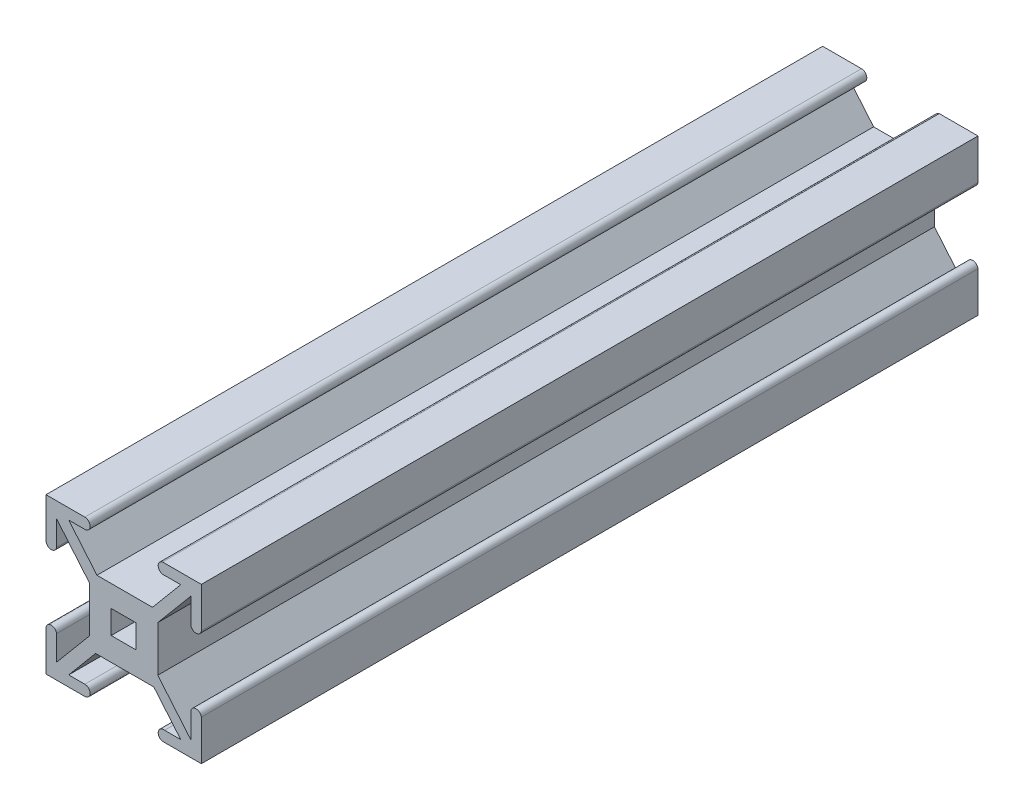
SolidWorks part; units mm, degrees
ref_plane "Front Plane" through (0, 0, 0) normal (0, 0, 1) x (1, 0, 0)
ref_plane "Top Plane" through (0, 0, 0) normal (0, 1, 0) x (1, 0, 0)
ref_plane "Right Plane" through (0, 0, 0) normal (1, 0, 0) x (0, 0, -1)
sketch "Sketch1" plane through (0, 0, 0) normal (0, 0, 1) x (1, 0, 0)
  line L1 (-21.0591, 25) -> (28.9409, 25)
  line L2 (-21.0591, 25) -> (-21.0591, -25)
  line L3 (-21.0591, -25) -> (28.9409, -25)
  line L4 (28.9409, 25) -> (28.9409, -25)
  dimension "D1" = 50
  dimension "D2" = 50
extrude "Boss-Extrude1" add sketch "Sketch1" along normal blind 250
sketch "Sketch2" plane through (0, 0, 0) normal (0, 0, -1) x (-1, 0, 0)
  line L1 (-12.9409, 9) -> (5.0591, 9)
  line L2 (-12.9409, 9) -> (-12.9409, -9)
  line L3 (-12.9409, -9) -> (5.0591, -9)
  line L4 (5.0591, 9) -> (5.0591, -9)
  line L8 (-28.9409, -25) -> (-28.9409, 25) construction
  line L9 (21.0591, 25) -> (21.0591, -25) construction
  line L10 (21.0591, -25) -> (-28.9409, -25) construction
  line L11 (-28.9409, 25) -> (21.0591, 25) construction
  dimension "D1" = 16
  dimension "D2" = 16
  dimension "D3" = 16
  dimension "D4" = 16
extrude "Cut-Extrude2" cut sketch "Sketch2" against normal blind 287
sketch "Sketch3" plane through (0, 0, 0) normal (0, 0, -1) x (-1, 0, 0)
  line L1 (-22.3163, 21.5842) -> (-17.1163, 21.5842)
  line L9 (-28.9409, 25) -> (-16.4651, 25)
  line L10 (-28.9409, 25) -> (21.0591, 25) construction
  line L11 (-17.2817, 15.5842) -> (-22.3163, 21.5842)
  line L12 (-28.9409, 25) -> (-28.9409, 12.5)
  line L13 (-28.9409, -25) -> (-28.9409, 25) construction
  line L15 (8.7183, 15.5842) -> (13.7529, 21.5842)
  line L16 (13.7529, 21.5842) -> (8.5591, 21.5842)
  line L17 (-25.5409, 20.0034) -> (-18.5395, 11.6595)
  line L18 (8.5591, 25) -> (21.0591, 25)
  line L19 (-25.5409, 20.0034) -> (-25.5409, 12.0034)
  line L20 (10.6577, 11.6595) -> (7.0357, 7.3429)
  line L21 (17.6591, 20.0034) -> (10.6577, 11.6595)
  line L22 (17.6591, 20.0034) -> (17.6591, 12.0034)
  line L23 (21.0591, 25) -> (21.0591, 12.5)
  line L24 (-18.5395, 11.6595) -> (-14.9175, 7.3429)
  line L26 (-25.5409, -20.0034) -> (-18.5395, -11.6595)
  line L27 (-25.5409, -20.0034) -> (-25.5409, -12.0034)
  line L28 (-28.9409, -25) -> (-28.9409, -12.5)
  line L29 (-28.9409, -25) -> (-16.4651, -25)
  line L30 (-22.3163, -21.5842) -> (-17.1163, -21.5842)
  line L31 (-17.2817, -15.5842) -> (-22.3163, -21.5842)
  line L32 (17.6591, -20.0034) -> (10.6577, -11.6595)
  line L33 (17.6591, -20.0034) -> (17.6591, -12.0034)
  line L34 (21.0591, -25) -> (21.0591, -12.5)
  line L35 (8.5591, -25) -> (21.0591, -25)
  line L36 (13.7529, -21.5842) -> (8.5591, -21.5842)
  line L37 (8.7183, -15.5842) -> (13.7529, -21.5842)
  line L40 (-13.217, 10.7401) -> (4.6536, 10.7401)
  line L41 (-14.9175, 7.3429) -> (-14.9175, -7.3429)
  line L42 (-13.6531, -11.2599) -> (5.0898, -11.2599)
  line L43 (7.0357, 7.3429) -> (7.0357, -7.3429)
  line L44 (-14.9175, 10.7401) -> (7.0357, -11.2599) construction
  line L45 (-14.9175, -11.2599) -> (7.0357, 10.7401) construction
  line L46 (-17.2817, 15.5842) -> (-13.217, 10.7401)
  line L47 (8.7183, 15.5842) -> (4.6536, 10.7401)
  line L48 (8.7183, -15.5842) -> (5.0898, -11.2599)
  line L49 (-18.5395, -11.6595) -> (-14.9175, -7.3429)
  line L50 (-17.2817, -15.5842) -> (-13.6531, -11.2599)
  line L51 (10.6577, -11.6595) -> (7.0357, -7.3429)
  arc A0 (8.5591, 21.5842) -> (8.5591, 25) centre (8.5591, 23.2921) cw
  arc A1 (-16.4651, 25) -> (-17.1163, 21.5842) centre (-16.7907, 23.2921) cw
  arc A2 (-25.5409, 12.0034) -> (-28.9409, 12.5) centre (-27.2409, 12.2517) cw
  arc A3 (17.6591, 12.0034) -> (21.0591, 12.5) centre (19.3591, 12.2517) ccw
  arc A4 (-25.5409, -12.0034) -> (-28.9409, -12.5) centre (-27.2409, -12.2517) ccw
  arc A5 (-16.4651, -25) -> (-17.1163, -21.5842) centre (-16.7907, -23.2921) ccw
  arc A6 (17.6591, -12.0034) -> (21.0591, -12.5) centre (19.3591, -12.2517) cw
  arc A7 (8.5591, -21.5842) -> (8.5591, -25) centre (8.5591, -23.2921) ccw
  point P23 (-3.9409, -0.2599)
extrude "Cut-Extrude5" cut sketch "Sketch3" against normal blind 287 flip side to cut
sketch "Sketch4" plane through (0, 0, 0) normal (0, 0, -1) x (-1, 0, 0)
  line L1 (-12.9409, 9) -> (5.0591, 9)
  line L2 (-12.9409, 9) -> (-12.9409, -9)
  line L3 (-12.9409, -9) -> (5.0591, -9)
  line L4 (5.0591, 9) -> (5.0591, -9)
extrude "Boss-Extrude2" add sketch "Sketch4" against normal blind 250
sketch "Sketch5" plane through (0, 0, 0) normal (0, 0, -1) x (-1, 0, 0)
  line L1 (-7.9175, 3.7766) -> (0.0825, 3.7766)
  line L2 (-7.9175, 3.7766) -> (-7.9175, -3.7766)
  line L3 (-7.9175, -3.7766) -> (0.0825, -3.7766)
  line L4 (0.0825, 3.7766) -> (0.0825, -3.7766)
  line L5 (-7.9175, 3.7766) -> (0.0825, -3.7766) construction
  line L6 (-7.9175, -3.7766) -> (0.0825, 3.7766) construction
  point P0 (-3.9175, 0)
extrude "Cut-Extrude6" cut sketch "Sketch5" against normal blind 250
